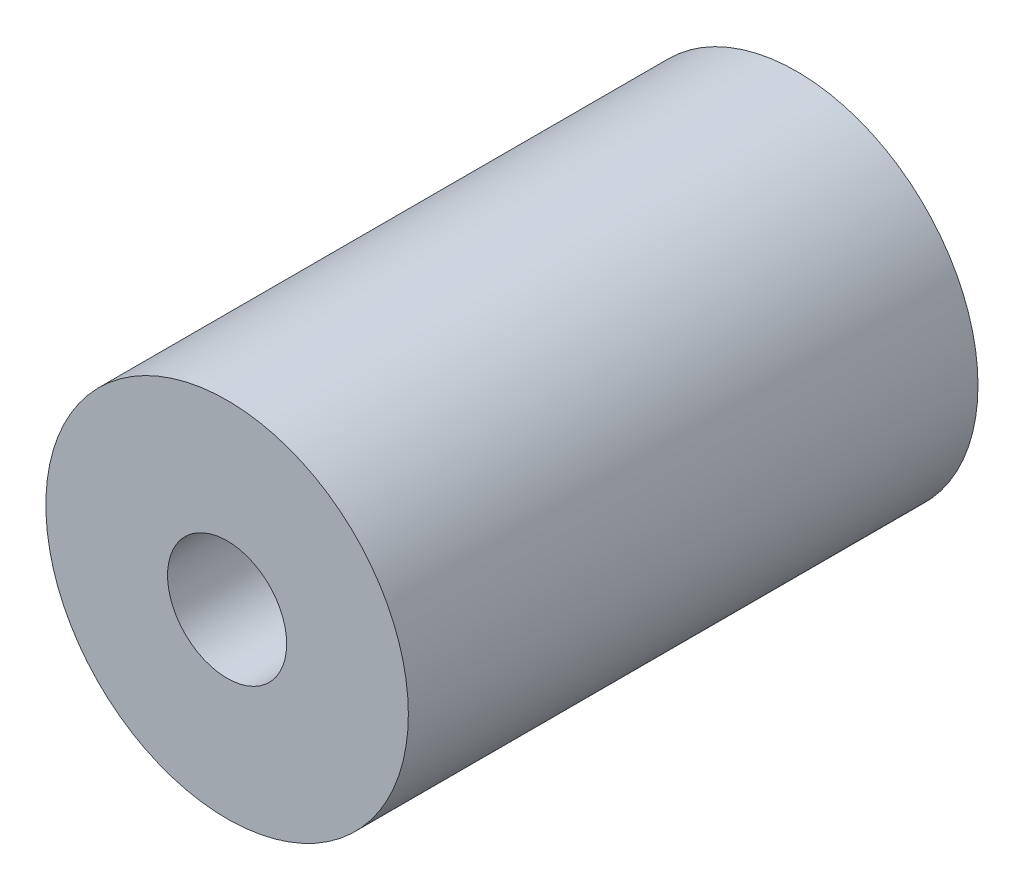
SolidWorks part; units mm, degrees
ref_plane "Alzado" through (0, 0, 0) normal (0, 0, 1) x (1, 0, 0)
ref_plane "Planta" through (0, 0, 0) normal (0, 1, 0) x (1, 0, 0)
ref_plane "Vista lateral" through (0, 0, 0) normal (1, 0, 0) x (0, 0, -1)
sketch "Croquis1" plane through (0, 0, 0) normal (0, 0, 1) x (1, 0, 0)
  circle A0 centre (0, 0) radius 3.5
  dimension "D1" = 7
extrude "Saliente-Extruir1" add sketch "Croquis1" along normal blind 11
sketch "Croquis3" plane through (0, 0, 0) normal (0, 0, -1) x (-1, 0, 0)
  line L1 (1.5497, 2.6849) -> (-1.5503, 2.6845)
  line L2 (-1.5503, 2.6845) -> (-3.1, -0.0004)
  line L3 (-3.1, -0.0004) -> (-1.5497, -2.6849)
  line L4 (-1.5497, -2.6849) -> (1.5503, -2.6845)
  line L5 (1.5503, -2.6845) -> (3.1, 0.0004)
  line L6 (3.1, 0.0004) -> (1.5497, 2.6849)
  circle A0 centre (0, 0) radius 2.6847 construction
  dimension "D1" = 3.1
extrude "Cortar-Extruir1" cut sketch "Croquis3" against normal blind 7
sketch "Croquis4" plane through (0, 0, 11) normal (0, 0, 1) x (1, 0, 0)
  circle A0 centre (0, 0) radius 1.15
  dimension "D1" = 2.3
extrude "Cortar-Extruir2" cut sketch "Croquis4" against normal blind 2.3
